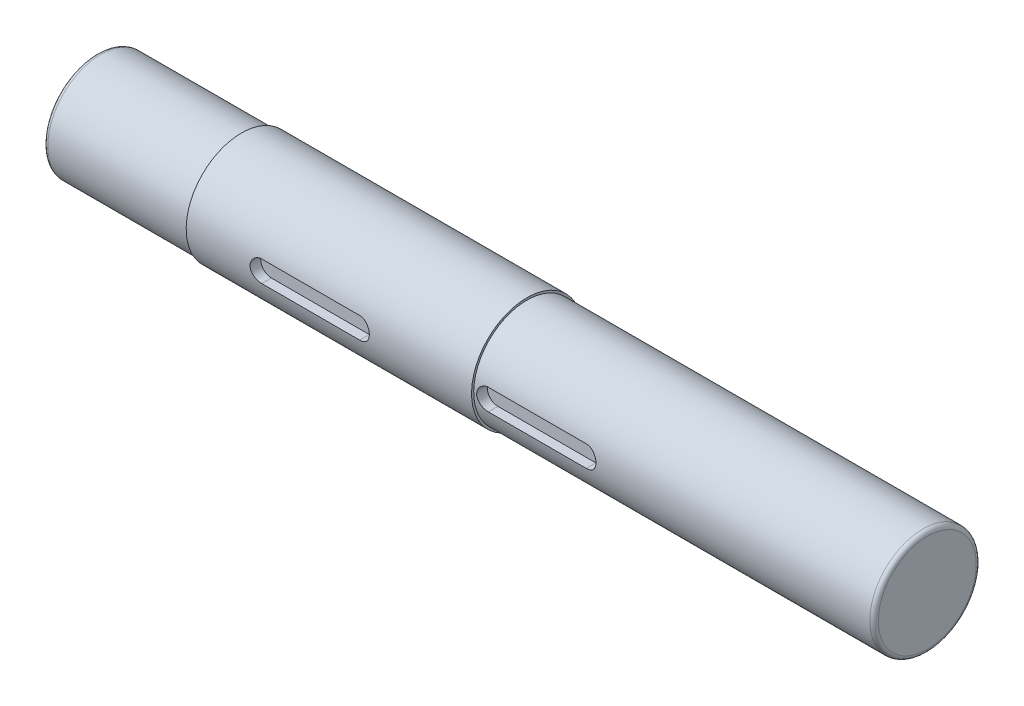
SolidWorks part; units mm, degrees
ref_plane "Front Plane" through (0, 0, 0) normal (0, 0, 1) x (1, 0, 0)
ref_plane "Top Plane" through (0, 0, 0) normal (0, 1, 0) x (1, 0, 0)
ref_plane "Right Plane" through (0, 0, 0) normal (1, 0, 0) x (0, 0, -1)
sketch "Sketch1" plane through (0, 0, 0) normal (0, 0, 1) x (1, 0, 0)
  line L0 (0, 0) -> (160.0434, 0) construction
  line L1 (16.7771, 0) -> (16.7771, 12.5)
  line L2 (16.7771, 12.5) -> (50.7771, 12.5)
  line L3 (50.7771, 12.5) -> (50.7771, 13)
  line L4 (50.7771, 13) -> (117.7771, 13)
  line L5 (117.7771, 13) -> (117.7771, 12.5)
  line L6 (117.7771, 12.5) -> (211.7771, 12.5)
  line L7 (211.7771, 12.5) -> (211.7771, 0)
  line L8 (16.7771, 0) -> (211.7771, 0)
  dimension "D1" = 34
  dimension "D2" = 67
  dimension "D3" = 94
  dimension "D4" = 0.5
  dimension "D5" = 0.5
  dimension "D6" = 12.5
  dimension "D7" = 12.5
revolve "Revolve1" add sketch "Sketch1" angle 360 about L0
ref_plane "Plane2" through (0, 0, 12.5) normal (0, 0, 1) x (1, 0, 0)
sketch "Sketch2" plane through (0, 0, 12.5) normal (0, 0, 1) x (1, 0, 0)
  line L0 (113.2702, 0) -> (216.3093, 0) construction
  line L1 (120.9771, 0) -> (143.9771, 0) construction
  line L2 (120.9771, 2.5) -> (143.9771, 2.5)
  line L3 (120.9771, -2.5) -> (143.9771, -2.5)
  line L4 (211.7771, -12.5) -> (211.7771, 12.5) construction
  arc A0 (120.9771, 2.5) -> (120.9771, -2.5) centre (120.9771, 0) ccw
  arc A1 (143.9771, -2.5) -> (143.9771, 2.5) centre (143.9771, 0) ccw
  point P5 (132.4771, 0)
  dimension "D1" = 23
  dimension "D2" = 5
  dimension "D3" = 90.8
extrude "Cut-Extrude2" cut sketch "Sketch2" against normal blind 2.5
ref_plane "Plane4" through (0, 0, 13) normal (0, 0, 1) x (1, 0, 0)
sketch "Sketch3" plane through (0, 0, 13) normal (0, 0, 1) x (1, 0, 0)
  line L0 (41.67, 0) -> (120.9771, 0) construction
  line L1 (68.2771, 0) -> (91.2771, 0) construction
  line L2 (68.2771, 2.5) -> (91.2771, 2.5)
  line L3 (68.2771, -2.5) -> (91.2771, -2.5)
  line L4 (117.7771, -13) -> (117.7771, 13) construction
  line L5 (50.7771, 13) -> (50.7771, -13) construction
  arc A0 (68.2771, 2.5) -> (68.2771, -2.5) centre (68.2771, 0) ccw
  arc A1 (91.2771, -2.5) -> (91.2771, 2.5) centre (91.2771, 0) ccw
  point P5 (79.7771, 0)
  point P10 (93.7771, 0)
  point P13 (65.7771, 0)
  dimension "D1" = 23
  dimension "D2" = 5
  dimension "D3" = 24
  dimension "D4" = 15
extrude "Cut-Extrude3" cut sketch "Sketch3" against normal blind 2.5
fillet "Fillet1" radius 1 1 edges at (211.7771, -12.5, 0)
fillet "Fillet2" radius 1 1 edges at (16.7771, -12.5, 0)
